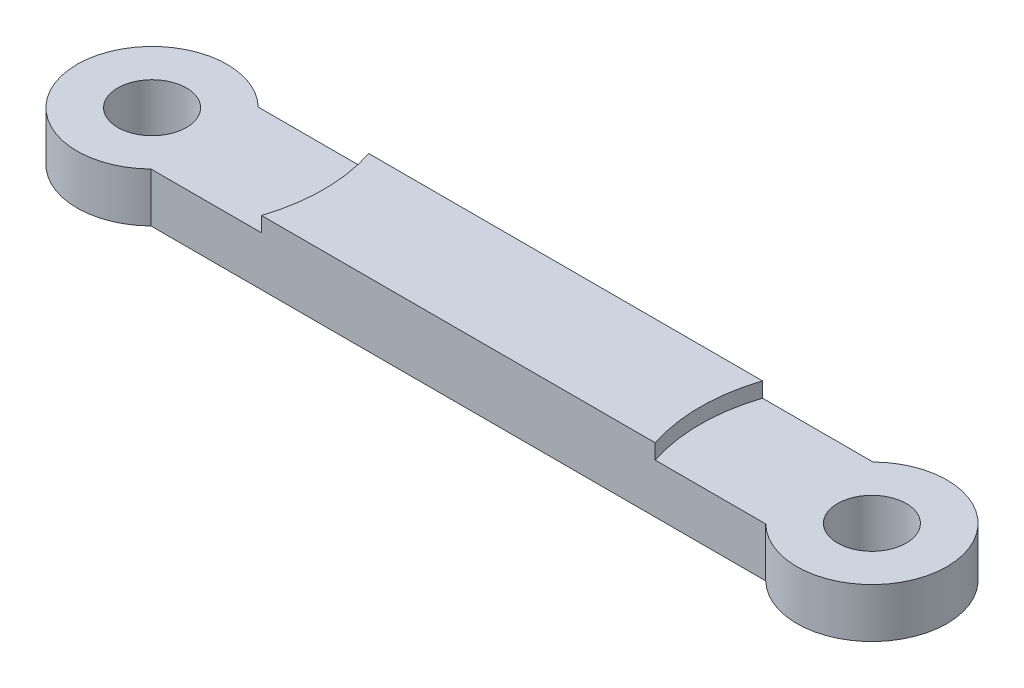
SolidWorks part; units mm, degrees
ref_plane "Front Plane" through (0, 0, 0) normal (0, 0, 1) x (1, 0, 0)
ref_plane "Top Plane" through (0, 0, 0) normal (0, 1, 0) x (1, 0, 0)
ref_plane "Right Plane" through (0, 0, 0) normal (1, 0, 0) x (0, 0, -1)
sketch "Sketch1" plane through (0, 0, 0) normal (0, 1, 0) x (1, 0, 0)
  line L0 (-13.7104, 1.6905) -> (0, 0) construction
  line L1 (-14.3255, -2.5) -> (14.3255, -2.5)
  line L3 (-14.3255, 2.5) -> (14.3255, 2.5)
  line L5 (-20.275, -2.5) -> (0, 0) construction
  line L6 (-20.275, 2.5) -> (-19.0404, 2.3478) construction
  line L7 (19.0404, 2.3478) -> (20.275, 2.5) construction
  line L8 (19.3372, -2.3844) -> (20.275, -2.5) construction
  circle A0 centre (16.775, 0) radius 1.5
  circle A1 centre (-16.775, 0) radius 1.5
  arc A6 (-14.3255, 2.5) -> (-14.3255, -2.5) centre (-16.775, 0) ccw
  arc A7 (14.3255, -2.5) -> (14.3255, 2.5) centre (16.775, 0) ccw
  point P0 (0, 0)
  dimension "D3" = 3
  dimension "D6" = 3
  dimension "D1" = 5
  dimension "D5" = 2.5
  dimension "D7" = 33.55
  dimension "D8" = 2.5
extrude "Boss-Extrude1" add sketch "Sketch1" along normal blind 3
sketch "Sketch2" plane through (0, 3, 0) normal (0, 1, 0) x (1, 0, 0)
  circle A0 centre (-16.775, 0) radius 8
  circle A1 centre (16.775, 0) radius 8
  dimension "D1" = 16
  dimension "D2" = 16
extrude "Cut-Extrude1" cut sketch "Sketch2" against normal blind 0.7
sketch "Sketch3" plane through (0, 2.3, 0) normal (0, 1, 0) x (1, 0, 0)
  circle A0 centre (-16.775, 0) radius 1.6
  circle A1 centre (16.775, 0) radius 1.6
  dimension "D1" = 3.2
  dimension "D2" = 3.2
extrude "Cut-Extrude3" cut sketch "Sketch3" against normal blind 10.5
